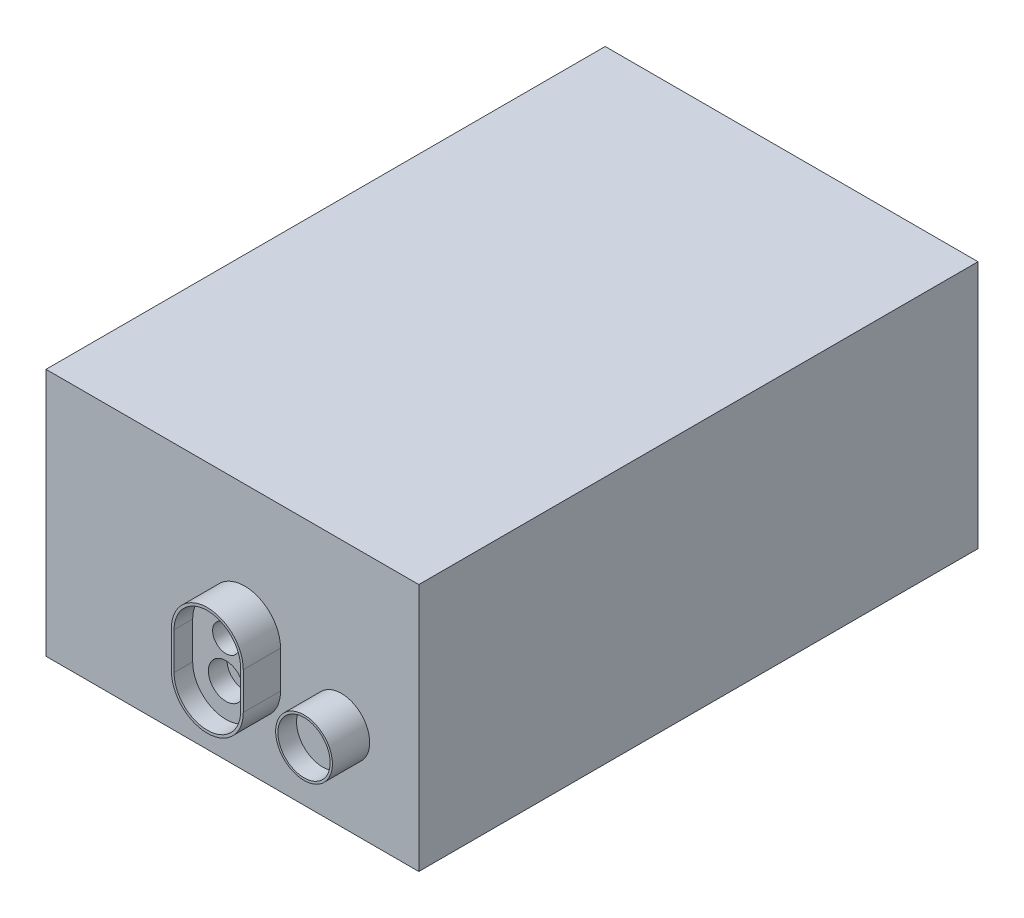
SolidWorks part; units mm, degrees
material "1060 Alloy"
ref_plane "Front Plane" through (0, 0, 0) normal (0, 0, 1) x (1, 0, 0)
ref_plane "Top Plane" through (0, 0, 0) normal (0, 1, 0) x (1, 0, 0)
ref_plane "Right Plane" through (0, 0, 0) normal (1, 0, 0) x (0, 0, -1)
sketch "Sketch1" plane through (0, 0, 0) normal (0, 0, 1) x (1, 0, 0)
  line L1 (-150, 100) -> (150, 100)
  line L2 (-150, 100) -> (-150, -100)
  line L3 (-150, -100) -> (150, -100)
  line L4 (150, 100) -> (150, -100)
  line L5 (-150, 100) -> (150, -100) construction
  line L6 (-150, -100) -> (150, 100) construction
  point P0 (0, 0)
extrude "Boss-Extrude1" add sketch "Sketch1" along normal blind 450
shell "Shell1" thickness 10
sketch "Sketch2" plane through (0, 0, 450) normal (0, 0, 1) x (1, 0, 0)
  line L0 (-19.0656, 0) -> (-19.0656, -29.8284)
  line L1 (9.8403, 28.9059) -> (9.8403, -58.7342) construction
  line L2 (38.7462, 0) -> (38.7462, -29.8284)
  line L3 (-16.9641, 0) -> (-16.9641, -29.8284)
  line L4 (36.6447, 0) -> (36.6447, -29.8284)
  arc A0 (38.7462, 0) -> (-19.0656, 0) centre (9.8403, 0) ccw
  arc A1 (-19.0656, -29.8284) -> (38.7462, -29.8284) centre (9.8403, -29.8284) ccw
  circle A2 centre (87.6401, -29.8284) radius 22.849
  arc A3 (36.6447, 0) -> (-16.9641, 0) centre (9.8403, 0) ccw
  arc A4 (-16.9641, -29.8284) -> (36.6447, -29.8284) centre (9.8403, -29.8284) ccw
  circle A5 centre (87.6401, -29.8284) radius 21.0394
extrude "Boss-Extrude2" add sketch "Sketch2" along normal blind 30
sketch "Sketch5" plane through (0, 0, 450) normal (0, 0, 1) x (1, 0, 0)
  line L2 (-16.9641, 0) -> (-16.9641, -29.8284)
  line L3 (36.6447, -29.8284) -> (36.6447, 0)
  line L4 (-16.9641, 0) -> (-16.9641, -29.8284)
  line L5 (36.6447, -29.8284) -> (36.6447, 0)
  circle A0 centre (9.8403, 0) radius 10.7628
  circle A1 centre (9.8403, -29.8284) radius 14.1755
  arc A2 (36.6447, 0) -> (-16.9641, 0) centre (9.8403, 0) ccw
  arc A3 (-16.9641, -29.8284) -> (36.6447, -29.8284) centre (9.8403, -29.8284) ccw
  arc A4 (36.6447, 0) -> (-16.9641, 0) centre (9.8403, 0) ccw
  arc A5 (-16.9641, -29.8284) -> (36.6447, -29.8284) centre (9.8403, -29.8284) ccw
  dimension "D1" = 0
extrude "Boss-Extrude3" add sketch "Sketch5" along normal blind 15
sketch "Sketch6" plane through (0, 0, 450) normal (0, 0, 1) x (1, 0, 0)
  circle A1 centre (87.6401, -29.8284) radius 21.0394
  circle A2 centre (87.6401, -29.8284) radius 21.0394
  dimension "D1" = 0
extrude "Boss-Extrude4" add sketch "Sketch6" along normal blind 15
